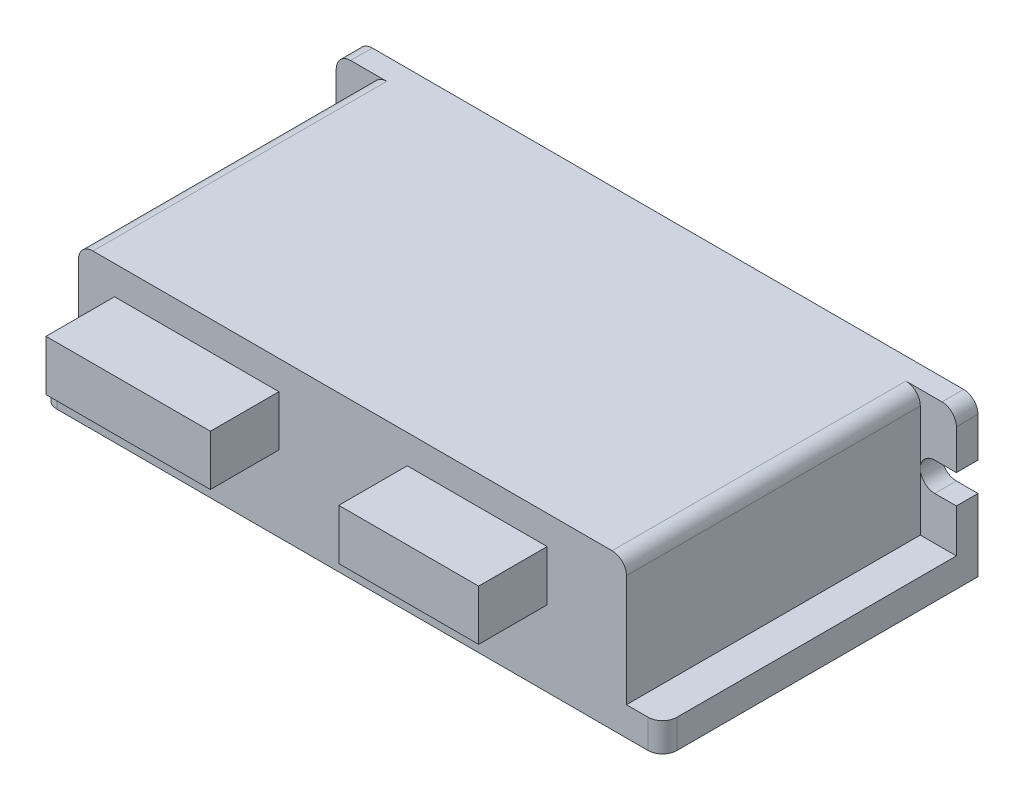
SolidWorks part; units mm, degrees
ref_plane "Front" through (0, 0, 0) normal (0, 0, 1) x (1, 0, 0)
ref_plane "Top" through (0, 0, 0) normal (0, 1, 0) x (1, 0, 0)
ref_plane "Right" through (0, 0, 0) normal (1, 0, 0) x (0, 0, -1)
sketch "Sketch1" plane through (0, 0, 0) normal (0, 0, 1) x (1, 0, 0)
  line L1 (-43, 10.75) -> (43, 10.75)
  line L2 (-43, 10.75) -> (-43, -10.75)
  line L3 (-43, -10.75) -> (43, -10.75)
  line L4 (43, 10.75) -> (43, -10.75)
  line L5 (-43, 10.75) -> (43, -10.75) construction
  line L6 (-43, -10.75) -> (43, 10.75) construction
  point P0 (0, 0)
  dimension "D1" = 21.5
  dimension "D2" = 86
extrude "Boss-Extrude1" add sketch "Sketch1" along normal blind 43.75
sketch "Sketch2" plane through (0, 0, 43.75) normal (0, 0, 1) x (1, 0, 0)
  line L0 (-43, -10.75) -> (43, -10.75) construction
  line L1 (-43, 10.75) -> (-38, 10.75)
  line L2 (-43, 10.75) -> (-43, -6.75)
  line L3 (-43, -6.75) -> (-38, -6.75)
  line L4 (-38, 10.75) -> (-38, -6.75)
  line L5 (43, 10.75) -> (38, 10.75)
  line L6 (43, 10.75) -> (43, -6.75)
  line L7 (43, -6.75) -> (38, -6.75)
  line L8 (38, 10.75) -> (38, -6.75)
  dimension "D1" = 4
  dimension "D2" = 5
  dimension "D3" = 5
extrude "Cut-Extrude1" cut sketch "Sketch2" against normal offset from surface (40.75 mm away) 3 up to face at (0, 0, 0)
sketch "Sketch3" plane through (0, 0, 0) normal (0, 0, -1) x (-1, 0, 0)
  line L0 (-43, 1.25) -> (43, 1.25) construction
  line L1 (-43, -10.75) -> (-43, 10.75) construction
  line L2 (43, 10.75) -> (43, -10.75) construction
  line L3 (43, -10.75) -> (-43, -10.75) construction
  line L4 (40, 1.25) -> (47.6711, 1.25) construction
  line L5 (40, 3.25) -> (47.6711, 3.25)
  line L6 (40, -0.75) -> (47.6711, -0.75)
  line L7 (0, 10.75) -> (0, -10.75) construction
  line L8 (-43, 10.75) -> (43, 10.75) construction
  line L9 (-40, 1.25) -> (-47.6711, 1.25) construction
  line L10 (-40, 3.25) -> (-47.6711, 3.25)
  line L11 (-40, -0.75) -> (-47.6711, -0.75)
  arc A0 (40, 3.25) -> (40, -0.75) centre (40, 1.25) ccw
  arc A1 (47.6711, -0.75) -> (47.6711, 3.25) centre (47.6711, 1.25) ccw
  arc A2 (-40, 3.25) -> (-40, -0.75) centre (-40, 1.25) cw
  arc A3 (-47.6711, -0.75) -> (-47.6711, 3.25) centre (-47.6711, 1.25) cw
  point P10 (43.8356, 1.25)
  point P21 (-43.8356, 1.25)
  dimension "D3" = 3
  dimension "D1" = 12
  dimension "D2" = 4
extrude "Cut-Extrude2" cut sketch "Sketch3" against normal through all
fillet "Fillet1" radius 2 6 edges at (-43, -8.75, 43.75) (43, -8.75, 43.75) (-43, 10.75, 1.5) (43, 10.75, 1.5) (-38, 10.75, 23.375) (38, 10.75, 23.375)
sketch "Sketch4" plane through (0, 0, 43.75) normal (0, 0, 1) x (1, 0, 0)
  line L0 (-38, 3.25) -> (38, 3.25) construction
  line L1 (-38, 8.75) -> (-38, 1.25) construction
  line L2 (38, 8.75) -> (38, -6.75) construction
  line L3 (36, 10.75) -> (-36, 10.75) construction
  line L4 (-38, -6.75) -> (-38, 8.75) construction
  line L5 (-33, 6.75) -> (-10.2, 6.75)
  line L6 (-33, 6.75) -> (-33, -0.25)
  line L7 (-33, -0.25) -> (-10.2, -0.25)
  line L8 (-10.2, 6.75) -> (-10.2, -0.25)
  line L9 (-33, 6.75) -> (-10.2, -0.25) construction
  line L10 (-33, -0.25) -> (-10.2, 6.75) construction
  line L11 (7.6, 6.75) -> (27, 6.75)
  line L12 (7.6, 6.75) -> (7.6, -0.25)
  line L13 (7.6, -0.25) -> (27, -0.25)
  line L14 (27, 6.75) -> (27, -0.25)
  line L15 (7.6, 6.75) -> (27, -0.25) construction
  line L16 (7.6, -0.25) -> (27, 6.75) construction
  point P8 (-21.6, 3.25)
  point P13 (17.3, 3.25)
  dimension "D1" = 7.5
  dimension "D2" = 4
  dimension "D3" = 5
  dimension "D4" = 11
  dimension "D5" = 17.8
  dimension "D6" = 22.8
extrude "Boss-Extrude2" add sketch "Sketch4" along normal blind 9.5
